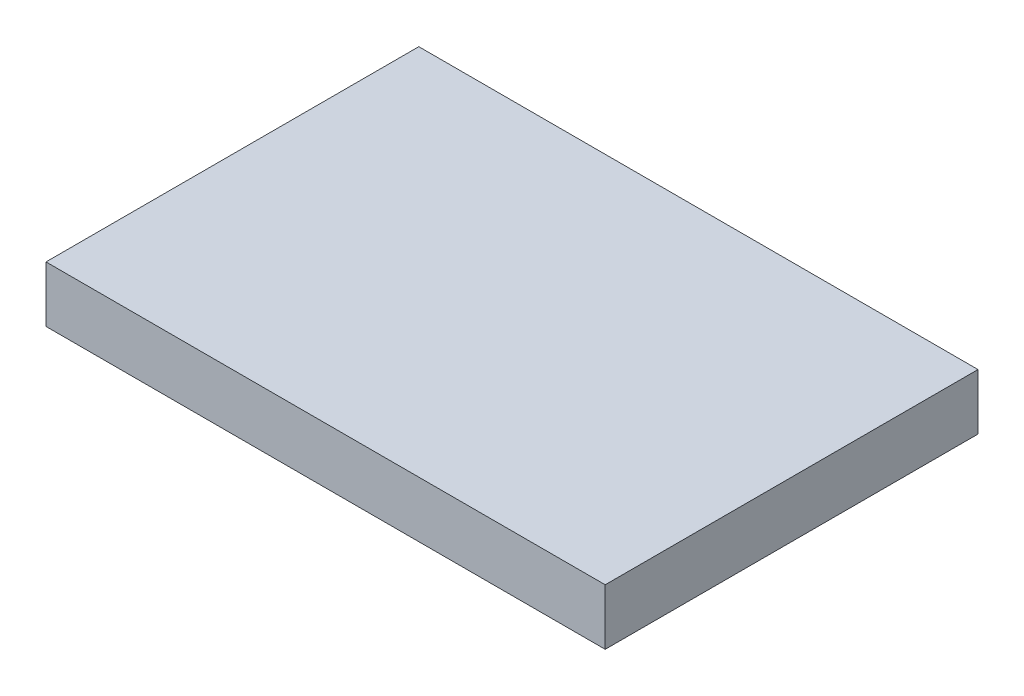
SolidWorks part; units mm, degrees
ref_plane "前视基准面" through (0, 0, 0) normal (0, 0, 1) x (1, 0, 0)
ref_plane "上视基准面" through (0, 0, 0) normal (0, 1, 0) x (1, 0, 0)
ref_plane "右视基准面" through (0, 0, 0) normal (1, 0, 0) x (0, 0, -1)
sketch "草图1" plane through (0, 0, 0) normal (0, 1, 0) x (1, 0, 0)
  line L1 (-38.0221, -4.9753) -> (-8.0221, -4.9753)
  line L2 (-38.0221, -4.9753) -> (-38.0221, -24.9753)
  line L3 (-38.0221, -24.9753) -> (-8.0221, -24.9753)
  line L4 (-8.0221, -4.9753) -> (-8.0221, -24.9753)
extrude "凸台-拉伸1" add sketch "草图1" along normal blind 3
